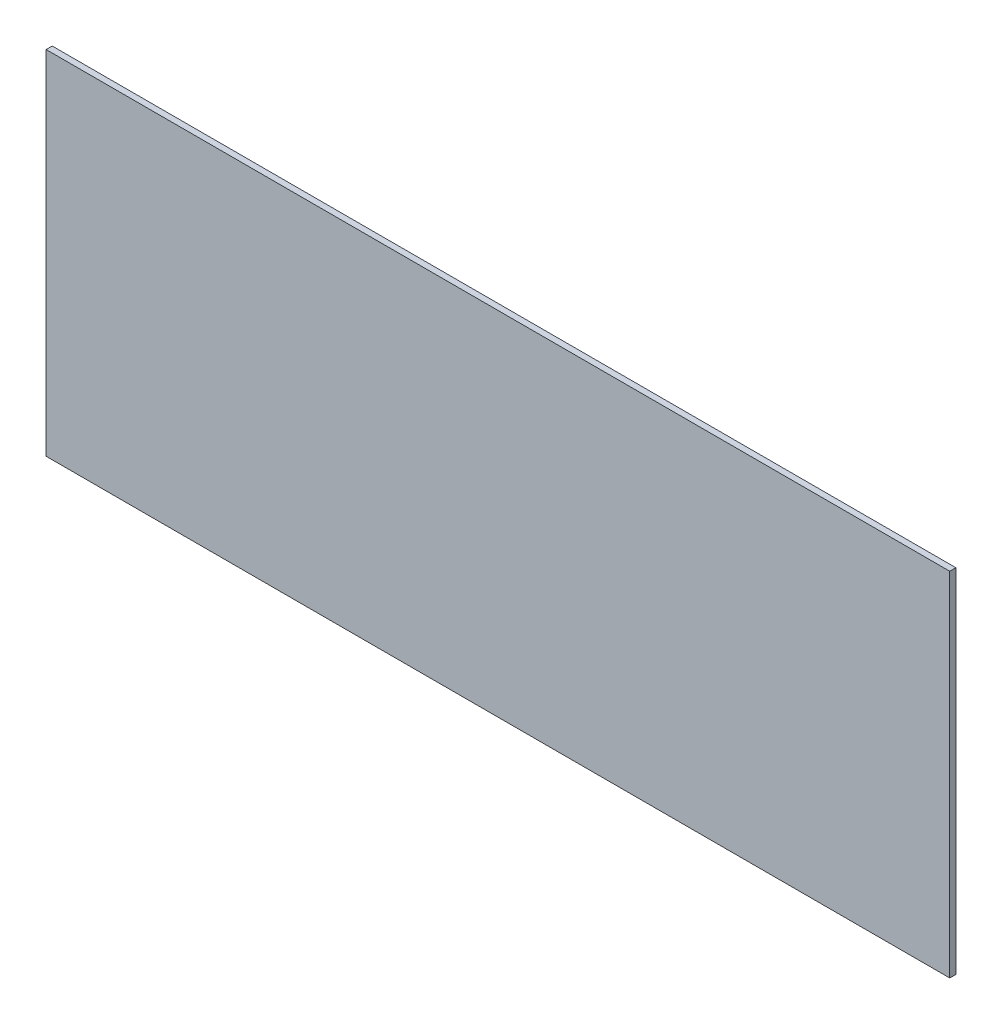
SolidWorks part; units mm, degrees
ref_plane "Front Plane" through (0, 0, 0) normal (0, 0, 1) x (1, 0, 0)
ref_plane "Top Plane" through (0, 0, 0) normal (0, 1, 0) x (1, 0, 0)
ref_plane "Right Plane" through (0, 0, 0) normal (1, 0, 0) x (0, 0, -1)
other "Configuration Table"
sketch "Sketch1" plane through (0, 0, 0) normal (0, 0, 1) x (1, 0, 0)
  line L1 (25, 25) -> (615, 25)
  line L2 (25, 25) -> (25, 255)
  line L3 (25, 255) -> (615, 255)
  line L4 (615, 25) -> (615, 255)
extrude "FKAP_cam_dis_4mm_1" add sketch "Sketch1" along normal blind 4 from offset 34 separate body
